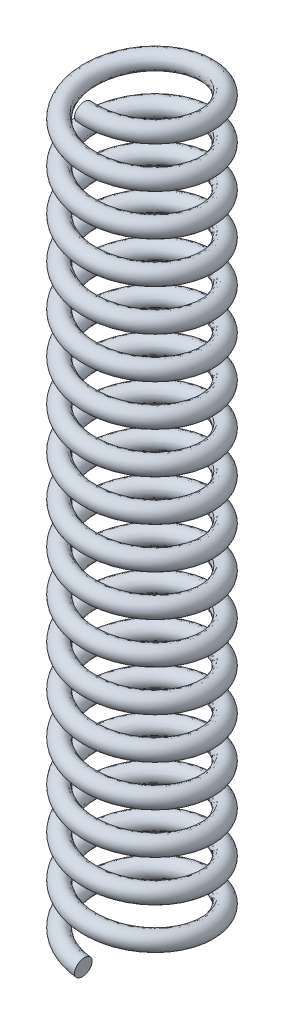
SolidWorks part; units mm, degrees
ref_plane "Front Plane" through (0, 0, 0) normal (0, 0, 1) x (1, 0, 0)
ref_plane "Top Plane" through (0, 0, 0) normal (0, 1, 0) x (1, 0, 0)
ref_plane "Right Plane" through (0, 0, 0) normal (1, 0, 0) x (0, 0, -1)
other "Configuration Table"
sketch "Sketch1" plane through (0, 0, 0) normal (0, 1, 0) x (1, 0, 0)
  circle A0 centre (0, 0) radius 4
curve "Coil_Helix" pitch 2.8096 height 50.5721 turns 18
sweep "Coil_Wire" add path "Coil_Helix" circular profile diameter 1.2 parameters "D3"=1.2
